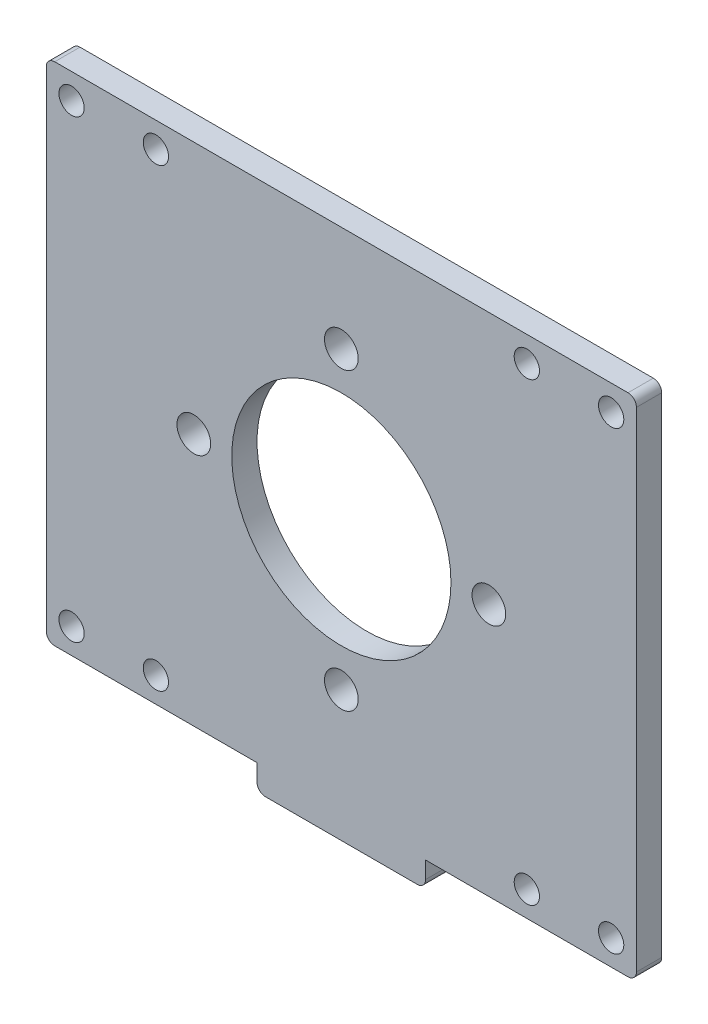
SolidWorks part; units mm, degrees
material "Thornel Mat VMA"
ref_plane "前视基准面" through (0, 0, 0) normal (0, 0, 1) x (1, 0, 0)
ref_plane "上视基准面" through (0, 0, 0) normal (0, 1, 0) x (1, 0, 0)
ref_plane "右视基准面" through (0, 0, 0) normal (1, 0, 0) x (0, 0, -1)
sketch "草图1" plane through (0, 0, 0) normal (0, 0, 1) x (1, 0, 0)
  line L1 (-35, -30) -> (35, -30)
  line L2 (-35, -30) -> (-35, 30)
  line L3 (-35, 30) -> (35, 30)
  line L4 (35, -30) -> (35, 30)
  line L5 (-35, -30) -> (35, 30) construction
  line L6 (-35, 30) -> (35, -30) construction
  point P0 (0, 0)
  dimension "D1" = 70
  dimension "D2" = 60
extrude "凸台-拉伸1" add sketch "草图1" along normal blind 3
sketch "草图2" plane through (0, 0, 3) normal (0, 0, 1) x (1, 0, 0)
  line L0 (0, 30) -> (0, -30) construction
  line L1 (35, 30) -> (-35, 30) construction
  line L2 (-35, -30) -> (35, -30) construction
  circle A0 centre (0, 0) radius 13
  dimension "D2" = 26
  dimension "D1" = 30
extrude "切除-拉伸1" cut sketch "草图2" against normal through all
sketch "草图3" plane through (0, 0, 3) normal (0, 0, 1) x (1, 0, 0)
  line L0 (-13, 0) -> (13, 0) construction
  line L1 (0, 13) -> (0, -13) construction
  circle A0 centre (0, 0) radius 13 construction
  circle A1 centre (0, 17.5) radius 2
  circle A2 centre (-17.5, 0) radius 2
  circle A3 centre (0, -17.5) radius 2
  circle A4 centre (17.5, 0) radius 2
  dimension "D2" = 4
  dimension "D4" = 4
  dimension "D1" = 17.5
  dimension "D3" = 17.5
extrude "切除-拉伸2" cut sketch "草图3" against normal through all
sketch "草图4" plane through (0, 0, 3) normal (0, 0, 1) x (1, 0, 0)
  line L0 (-35, -30) -> (35, -30) construction
  line L1 (-10, -30) -> (10, -30)
  line L2 (-10, -30) -> (-10, -33)
  line L3 (-10, -33) -> (10, -33)
  line L4 (10, -30) -> (10, -33)
  line L5 (0, -30) -> (0, -33) construction
  line L6 (0, 30) -> (0, -30) construction
  line L7 (35, 30) -> (-35, 30) construction
  dimension "D1" = 3
  dimension "D2" = 20
extrude "凸台-拉伸2" add sketch "草图4" against normal blind 3
sketch "草图5" plane through (0, 0, 3) normal (0, 0, 1) x (1, 0, 0)
  line L0 (0, 30) -> (0, -33) construction
  line L1 (35, 30) -> (-35, 30) construction
  line L2 (-10, -33) -> (10, -33) construction
  line L3 (-35, 30) -> (-35, -30) construction
  circle A0 centre (-32, 27) radius 1.5
  circle A1 centre (-22, 27) radius 1.5
  circle A2 centre (22, 27) radius 1.5
  circle A3 centre (32, 27) radius 1.5
  dimension "D3" = 3
  dimension "D1" = 3
  dimension "D2" = 3
  dimension "D4" = 10
extrude "切除-拉伸3" cut sketch "草图5" against normal through all
sketch "草图6" plane through (0, 0, 3) normal (0, 0, 1) x (1, 0, 0)
  line L0 (0, 30) -> (0, -33) construction
  line L1 (35, 30) -> (-35, 30) construction
  line L2 (-10, -33) -> (10, -33) construction
  line L3 (-35, 30) -> (-35, -30) construction
  line L4 (-35, -30) -> (-10, -30) construction
  circle A0 centre (-32, -27) radius 1.5
  circle A1 centre (-22, -27) radius 1.5
  circle A2 centre (22, -27) radius 1.5
  circle A3 centre (32, -27) radius 1.5
  dimension "D3" = 3
  dimension "D1" = 3
  dimension "D2" = 3
  dimension "D4" = 10
extrude "切除-拉伸4" cut sketch "草图6" against normal through all
fillet "圆角1" radius 1 6 edges at (-35, -30, 1.5) (-35, 30, 1.5) (35, 30, 1.5) (35, -30, 1.5) (10, -33, 1.5) (-10, -33, 1.5)
